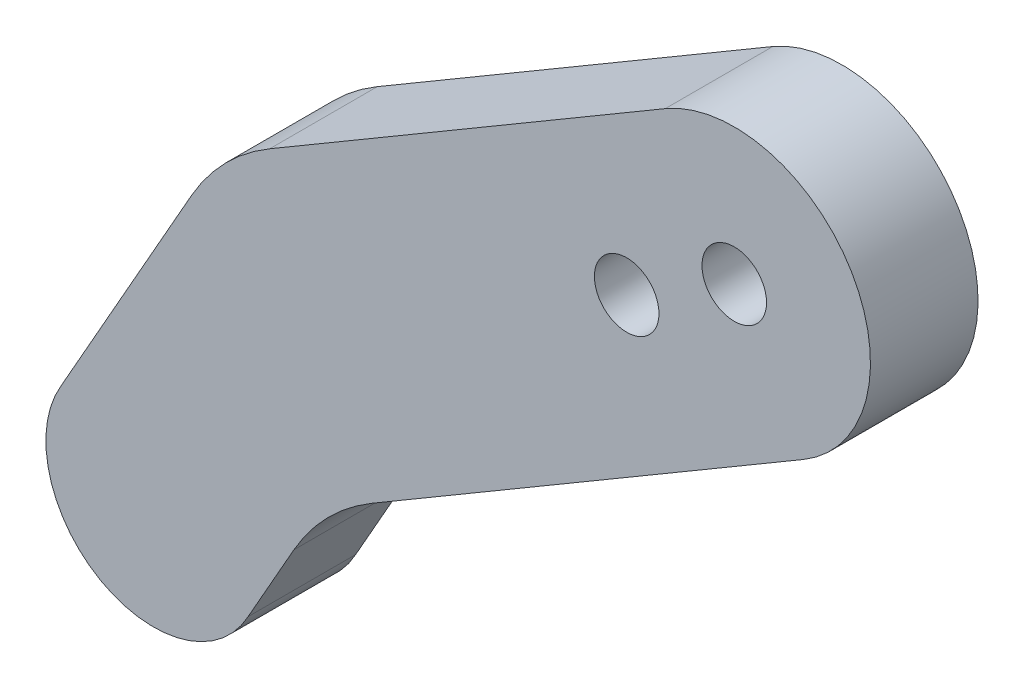
SolidWorks part; units mm, degrees
ref_plane "Front Plane" through (0, 0, 0) normal (0, 0, 1) x (1, 0, 0)
ref_plane "Top Plane" through (0, 0, 0) normal (0, 1, 0) x (1, 0, 0)
ref_plane "Right Plane" through (0, 0, 0) normal (1, 0, 0) x (0, 0, -1)
sketch "Sketch3" plane through (0, 0, 0) normal (0, 0, 1) x (1, 0, 0)
  line L0 (0, 0) -> (6.0764, 10.7178)
  line L1 (0, 0) -> (8.6992, -4.932) construction
  line L2 (8.6992, -4.932) -> (10.83, -1.1735)
  line L3 (9.7079, 14.4067) -> (28.0879, 25.2113)
  line L4 (28.0879, 25.2113) -> (34.5037, 14.2972) construction
  line L5 (14.4615, 2.5154) -> (34.5037, 14.2972)
  arc A0 (28.0879, 25.2113) -> (34.5037, 14.2972) centre (31.2958, 19.7542) cw
  arc A1 (0, 0) -> (8.6992, -4.932) centre (4.3053, -2.5441) ccw
  arc A2 (6.0764, 10.7178) -> (9.7079, 14.4067) centre (14.7756, 5.7859) cw
  arc A3 (10.83, -1.1735) -> (14.4615, 2.5154) centre (19.5292, -6.1054) cw
  point P10 (7.3979, 13.0488)
  point P13 (19.9017, -5.697)
  point P15 (12.1516, 1.1575)
  dimension "D7" = 5.0008
  dimension "D8" = 10
  dimension "D9" = 10
  dimension "D1" = 15
  dimension "D2" = 24
  dimension "D3" = 150
  dimension "D5" = 7
  dimension "D6" = 10
extrude "Boss-Extrude1" add sketch "Sketch3" along normal blind 5 contours L0 A1 L2 L5 A0 L3
sketch "Sketch4" plane through (0, 0, 5) normal (0, 0, 1) x (1, 0, 0)
  line L0 (28.0879, 25.2113) -> (34.5037, 14.2972) construction
  line L1 (31.2958, 19.7542) -> (25.8752, 16.5678) construction
  line L2 (28.0879, 25.2113) -> (34.5037, 14.2972) construction
  circle A0 centre (31.2958, 19.7542) radius 1.5
  arc A1 (34.5037, 14.2972) -> (28.0879, 25.2113) centre (31.2958, 19.7542) ccw construction
  circle A2 centre (26.2958, 16.815) radius 1.5
  point P9 (31.2958, 19.7542)
  dimension "D1" = 3
  dimension "D2" = 5
  dimension "D3" = 3
extrude "Cut-Extrude1" cut sketch "Sketch4" against normal blind 7
